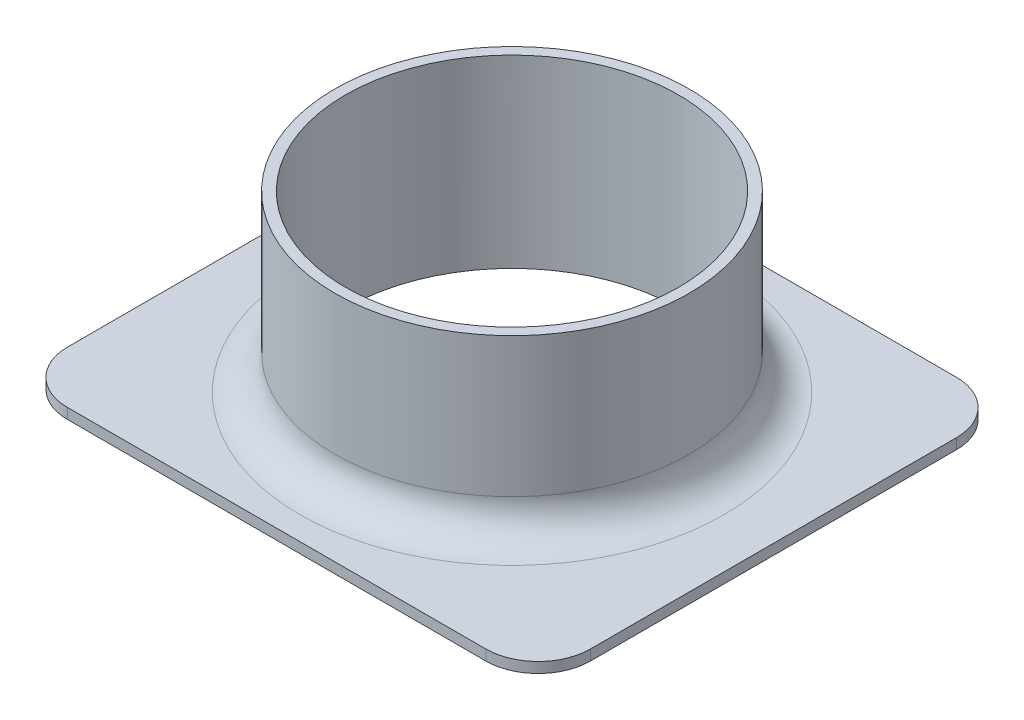
SolidWorks part; units mm, degrees
ref_plane "Plano frontal" through (0, 0, 0) normal (0, 0, 1) x (1, 0, 0)
ref_plane "Plano superior" through (0, 0, 0) normal (0, 1, 0) x (1, 0, 0)
ref_plane "Plano direito" through (0, 0, 0) normal (1, 0, 0) x (0, 0, -1)
sketch "Esboço1" plane through (0, 0, 0) normal (0, 1, 0) x (1, 0, 0)
  circle A0 centre (0, 0) radius 50.8
  dimension "D1" = 101.6
extrude "Extrusão-Fina1" add sketch "Esboço1" along normal blind 50 thin thin type one direction reverse wall 3
sketch "Esboço2" plane through (0, 0, 0) normal (0, -1, 0) x (1, 0, 0)
  line L1 (75, 67.5) -> (-75, 67.5)
  line L2 (75, 67.5) -> (75, -67.5)
  line L3 (75, -67.5) -> (-75, -67.5)
  line L4 (-75, 67.5) -> (-75, -67.5)
  line L5 (75, 67.5) -> (-75, -67.5) construction
  line L6 (75, -67.5) -> (-75, 67.5) construction
  point P0 (0, 0)
  dimension "D1" = 150
  dimension "D2" = 135
extrude "Ressalto-extrusão1" add sketch "Esboço2" along normal blind 3
fillet "Filete1" radius 10 1 edges at (0, 0, 50.8)
fillet "Filete2" radius 15 4 edges at (75, -1.5, 67.5) (-75, -1.5, 67.5) (-75, -1.5, -67.5) (75, -1.5, -67.5)
sketch "Esboço3" plane through (0, 0, 0) normal (0, 1, 0) x (1, 0, 0)
  circle A0 centre (0, 0) radius 47.8 construction
  circle A1 centre (0, 0) radius 47.8
extrude "Corte-extrusão1" cut sketch "Esboço3" against normal through all
